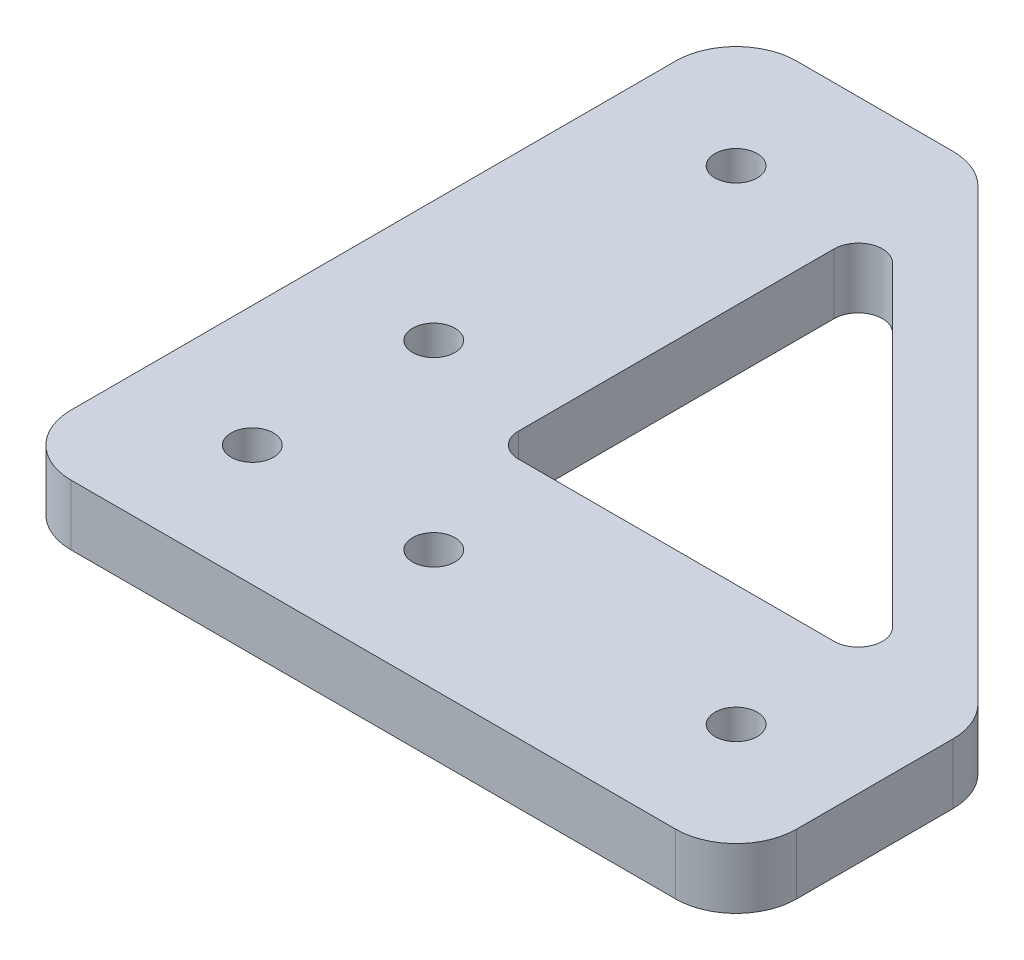
SolidWorks part; units mm, degrees
ref_plane "Plano frontal" through (0, 0, 0) normal (0, 0, 1) x (1, 0, 0)
ref_plane "Plano superior" through (0, 0, 0) normal (0, 1, 0) x (1, 0, 0)
ref_plane "Plano direito" through (0, 0, 0) normal (1, 0, 0) x (0, 0, -1)
sketch "Esboço1" plane through (0, 0, 0) normal (0, 1, 0) x (1, 0, 0)
  line L0 (0, 0) -> (0, 60)
  line L1 (0, 60) -> (20, 60)
  line L2 (20, 60) -> (60, 20)
  line L3 (60, 20) -> (60, 0)
  line L4 (60, 0) -> (0, 0)
  line L5 (10, 60) -> (10, 0) construction
  line L6 (60, 10) -> (0, 10) construction
  line L7 (52.9289, 20) -> (20, 52.9289)
  line L8 (20, 52.9289) -> (20, 20)
  line L9 (20, 20) -> (52.9289, 20)
  line L10 (20, 52.9289) -> (20, 60)
  line L11 (52.9289, 20) -> (60, 20)
  circle A0 centre (10, 50) radius 1.75
  circle A1 centre (10, 30) radius 1.75 construction
  circle A2 centre (30, 10) radius 1.75 construction
  circle A3 centre (50, 10) radius 1.75
  circle A4 centre (10, 10) radius 1.75
  dimension "D5" = 3.5
  dimension "D12" = 3.5
  dimension "D1" = 60
  dimension "D2" = 60
  dimension "D3" = 45
  dimension "D4" = 20
  dimension "D6" = 10
  dimension "D7" = 20
  dimension "D8" = 20
  dimension "D9" = 10
  dimension "D10" = 5
  dimension "D11" = 20
extrude "Ressalto-extrusão1" add sketch "Esboço1" along normal blind 5 contours L11 L9 L8 L10 L1 L0 L4 L3 A4 A3 A0 | L7 L11 L2 L10
sketch "Esboço2" plane through (0, 5, 0) normal (0, 1, 0) x (1, 0, 0)
  line L0 (30, 10) -> (50, 10) construction
  line L2 (20, 12.825) -> (60, 12.825)
  line L3 (20, 12.825) -> (20, 7.175)
  line L4 (20, 7.175) -> (60, 7.175)
  line L5 (60, 12.825) -> (60, 7.175)
  line L6 (20, 12.825) -> (60, 7.175) construction
  line L7 (20, 7.175) -> (60, 12.825) construction
  line L8 (10, 50) -> (10, 30) construction
  line L10 (7.175, 60) -> (12.825, 60)
  line L11 (7.175, 60) -> (7.175, 20)
  line L12 (7.175, 20) -> (12.825, 20)
  line L13 (12.825, 60) -> (12.825, 20)
  line L14 (7.175, 60) -> (12.825, 20) construction
  line L15 (7.175, 20) -> (12.825, 60) construction
  line L16 (60, 20) -> (60, 0) construction
  line L17 (0, 60) -> (20, 60) construction
  circle A4 centre (10, 50) radius 1.75 construction
  circle A5 centre (10, 50) radius 1.75
  circle A6 centre (50, 10) radius 1.75 construction
  circle A7 centre (50, 10) radius 1.75
  point P4 (40, 10)
  point P15 (10, 40)
  dimension "D1" = 5.65
  dimension "D2" = 5.65
  dimension "D3" = 20
extrude "Ressalto-extrusão2" [suppressed] add sketch "Esboço2" along normal blind 1
sketch "Esboço3" plane through (0, 0, 0) normal (0, -1, 0) x (1, 0, 0)
  line L0 (0, 0) -> (33.0815, -33.0815) construction
  line L2 (20, -46.163) -> (46.163, -20)
  line L5 (20, -46.163) -> (20, -20)
  line L6 (20, -20) -> (46.163, -20)
  line L8 (20, -20) -> (52.9289, -20) construction
  line L9 (20, -52.9289) -> (20, -20) construction
  circle A2 centre (27.0711, -27.0711) radius 3.4
  line M22 (20, -20) -> (52.9289, -20)
  line M27 (20, -52.9289) -> (20, -20)
  dimension "D1" = 6.8
  dimension "D2" = 10
  dimension "D3" = 8.5
extrude "Ressalto-extrusão3" [suppressed] add sketch "Esboço3" against normal up to surface (5 mm away) contours L0 L2 A2 M27 | L0 A2 L2 M22
fillet "Filete1" [suppressed] radius 10
fillet "Filete2" radius 2 3 edges at (20, 2.5, -52.9289) (20, 2.5, -20) (52.9289, 2.5, -20)
sketch "Esboço4" plane through (0, 0, 0) normal (0, -1, 0) x (1, 0, 0)
  line L0 (10, -10) -> (25, -10) construction
  line L1 (10, -10) -> (10, -25) construction
  circle A0 centre (10, -25) radius 1.75
  circle A1 centre (25, -10) radius 1.75
  dimension "D1" = 3.5
  dimension "D2" = 15
extrude "Corte-extrusão1" cut sketch "Esboço4" against normal blind 10
fillet "Filete3" radius 5 5 edges at (60, 2.5, -20) (20, 2.5, -60) (0, 2.5, -60) (0, 2.5, 0) (60, 2.5, 0)
